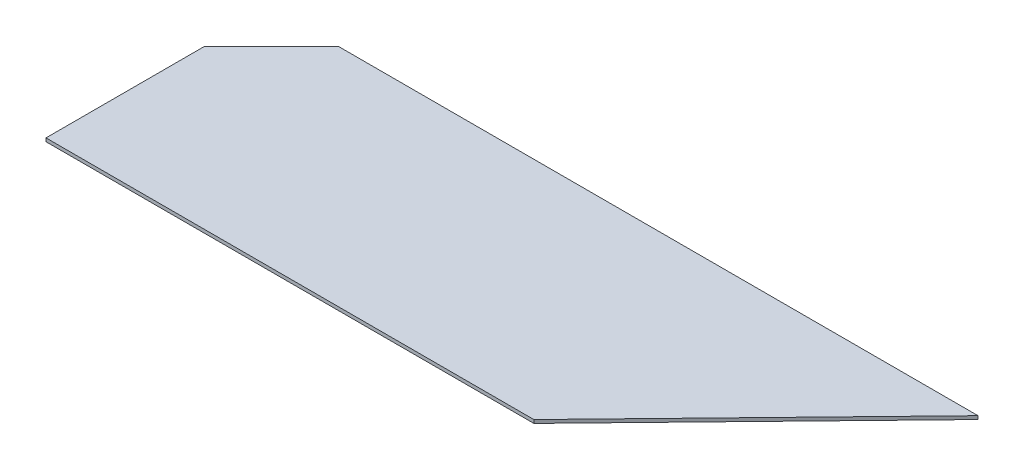
SolidWorks part; units mm, degrees
ref_plane "Front Plane" through (0, 0, 0) normal (0, 0, 1) x (1, 0, 0)
ref_plane "Top Plane" through (0, 0, 0) normal (0, 1, 0) x (1, 0, 0)
ref_plane "Right Plane" through (0, 0, 0) normal (1, 0, 0) x (0, 0, -1)
sketch "Sketch1" plane through (0, 0, 0) normal (0, 1, 0) x (1, 0, 0)
  line L0 (-23.2086, -19.3808) -> (49.2914, -19.3808)
  line L1 (49.2914, -19.3808) -> (81.7914, 14.1192)
  line L2 (-23.2086, -19.3808) -> (-23.2086, 4.1192)
  line L3 (-23.2086, 4.1192) -> (-13.2086, 14.1192)
  line L4 (-13.2086, 14.1192) -> (81.7914, 14.1192)
  point P7 (-10.1033, 14.1192)
  dimension "D1" = 72.5
  dimension "D2" = 33.5
  dimension "D3" = 23.5
  dimension "D4" = 95
  dimension "D5" = 10
extrude "Boss-Extrude1" add sketch "Sketch1" along normal blind 0.5
